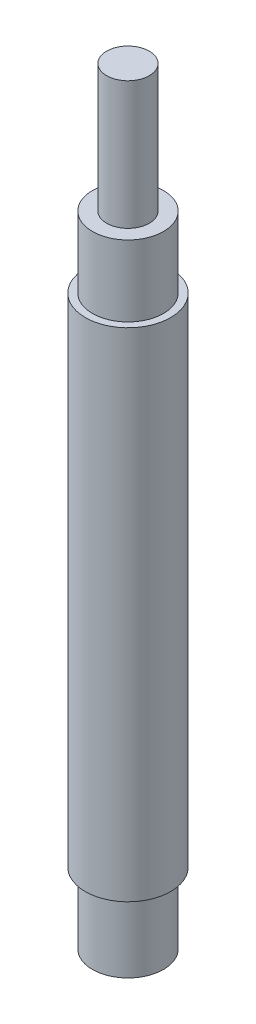
SolidWorks part; units mm, degrees
ref_plane "Front Plane" through (0, 0, 0) normal (0, 0, 1) x (1, 0, 0)
ref_plane "Top Plane" through (0, 0, 0) normal (0, 1, 0) x (1, 0, 0)
ref_plane "Right Plane" through (0, 0, 0) normal (1, 0, 0) x (0, 0, -1)
sketch "Sketch1" plane through (0, 0, 0) normal (0, 1, 0) x (1, 0, 0)
  circle A0 centre (0, 0) radius 5
  dimension "D1" = 10
extrude "Boss-Extrude1" add sketch "Sketch1" along normal blind 10
sketch "Sketch2" plane through (0, 10, 0) normal (0, 1, 0) x (1, 0, 0)
  circle A0 centre (0, 0) radius 6
  dimension "D1" = 12
extrude "Boss-Extrude2" add sketch "Sketch2" along normal blind 70
sketch "Sketch3" plane through (0, 80, 0) normal (0, 1, 0) x (1, 0, 0)
  circle A0 centre (0, 0) radius 5
  dimension "D1" = 10
extrude "Boss-Extrude3" add sketch "Sketch3" along normal blind 10
sketch "Sketch4" plane through (0, 90, 0) normal (0, 1, 0) x (1, 0, 0)
  circle A0 centre (0, 0) radius 3
  dimension "D1" = 6
extrude "Boss-Extrude4" add sketch "Sketch4" along normal blind 18
cosmetic thread "Cosmetic Thread1" parameters "D2"=5
